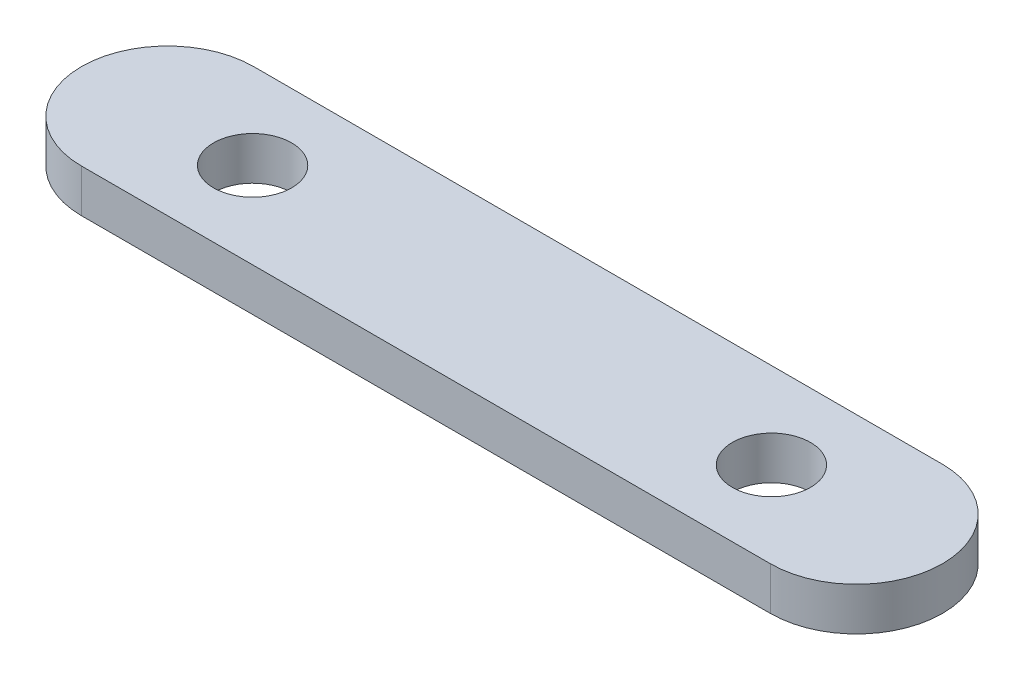
SolidWorks part; units mm, degrees
ref_plane "前视基准面" through (0, 0, 0) normal (0, 0, 1) x (1, 0, 0)
ref_plane "上视基准面" through (0, 0, 0) normal (0, 1, 0) x (1, 0, 0)
ref_plane "右视基准面" through (0, 0, 0) normal (1, 0, 0) x (0, 0, -1)
sketch "草图1" plane through (0, 0, 0) normal (0, 1, 0) x (1, 0, 0)
  line L0 (0, 0) -> (90670.8321, 0) construction
  line L1 (0, 0) -> (0, 90670.8321) construction
  line L2 (-80, 20) -> (80, 20)
  line L3 (80, -20) -> (-80, -20)
  arc A0 (80, 20) -> (80, -20) centre (80, 0) cw
  arc A1 (-80, -20) -> (-80, 20) centre (-80, 0) cw
  circle A2 centre (-60.25, 0) radius 9.0671
  circle A3 centre (60.25, 0) radius 9.0671
  dimension "D1" = 120.5
  dimension "D2" = 160
  dimension "D3" = 20
extrude "凸台-拉伸1" add sketch "草图1" along normal blind 10
